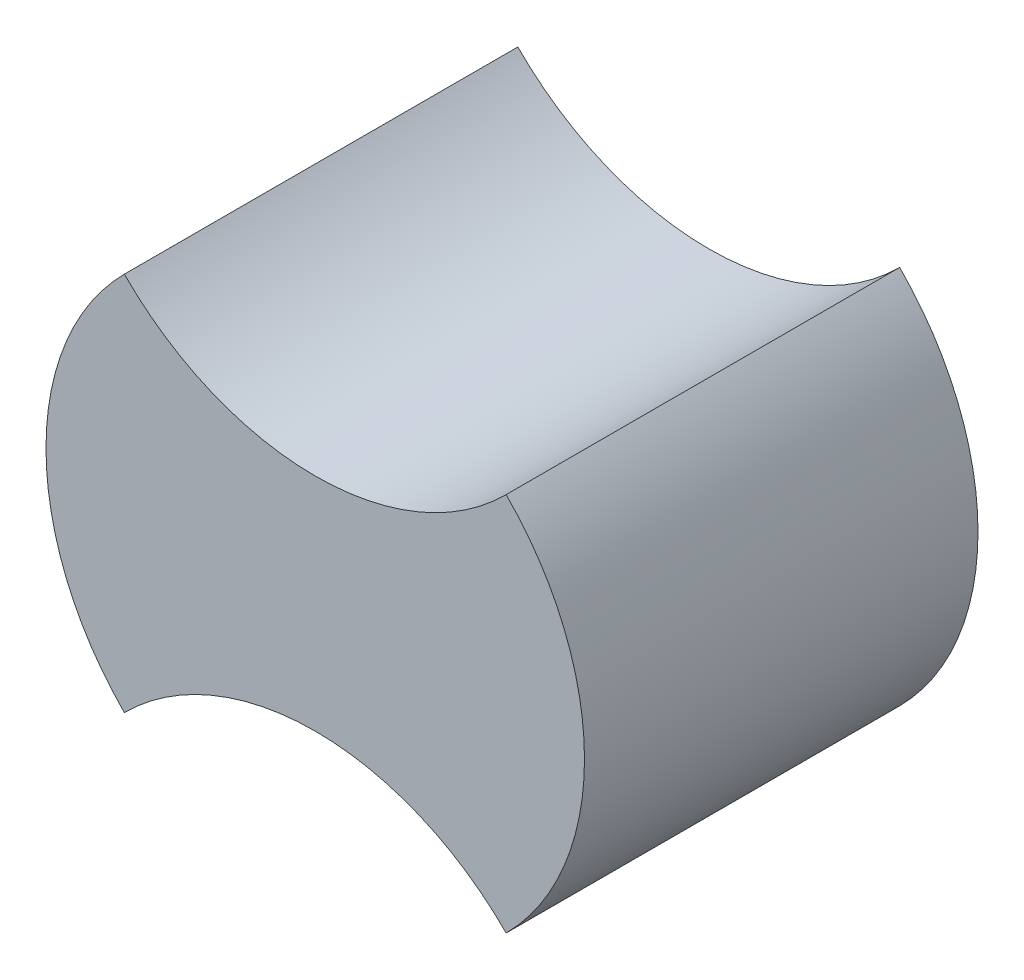
SolidWorks part; units mm, degrees
ref_plane "Front Plane" through (0, 0, 0) normal (0, 0, 1) x (1, 0, 0)
ref_plane "Top Plane" through (0, 0, 0) normal (0, 1, 0) x (1, 0, 0)
ref_plane "Right Plane" through (0, 0, 0) normal (1, 0, 0) x (0, 0, -1)
sketch "Sketch1" plane through (0, 0, 0) normal (0, 0, 1) x (1, 0, 0)
  line L0 (0, 0) -> (0, 35.7354) construction
  arc A0 (-27.6541, 27.5) -> (-27.6541, -27.5) centre (0, 0) ccw
  arc A2 (-27.6541, 27.5) -> (27.6541, 27.5) centre (0, 55) ccw
  arc A3 (27.6541, -27.5) -> (-27.6541, -27.5) centre (0, -55) ccw
  arc A4 (27.6541, -27.5) -> (27.6541, 27.5) centre (0, 0) ccw
  dimension "D1" = 78
  dimension "D2" = 78
  dimension "D3" = 78
  dimension "D4" = 55
  dimension "D5" = 55
extrude "Boss-Extrude1" add sketch "Sketch1" along normal blind 57 contours A2 A4 A3 A0
sketch "Sketch2" plane through (0, 0, 0) normal (0, 0, -1) x (-1, 0, 0)
  line L6 (16, 2) -> (1.5246, 5.8031)
  line L7 (-16, 2) -> (-1.5246, 5.8031)
  line L8 (-16, -2) -> (-1.5246, -5.8031)
  line L9 (16, -2) -> (1.5246, -5.8031)
  arc A1 (-1.5246, -5.8031) -> (1.5246, -5.8031) centre (0, 0) ccw
  arc A4 (-16, 2) -> (-16, -2) centre (-16, 0) ccw
  arc A5 (16, 2) -> (16, -2) centre (16, 0) cw
  arc A7 (1.5246, 5.8031) -> (-1.5246, 5.8031) centre (0, 0) ccw
  point P6 (0, 0)
extrude "Cut-Extrude1" cut sketch "Sketch2" against normal blind 3
equation "\"L\"= 78"
equation "\"D1@Sketch1\"=\"L\""
equation "\"D2@Sketch1\"=\"L\""
equation "\"D3@Sketch1\"=\"L\""
equation "\"D\"= 55"
equation "\"D5@Sketch1\"=\"D\""
equation "\"D4@Sketch1\"=\"D\""
equation "\"W\"= 57"
equation "\"D1@Boss-Extrude1\" = \"W\""
